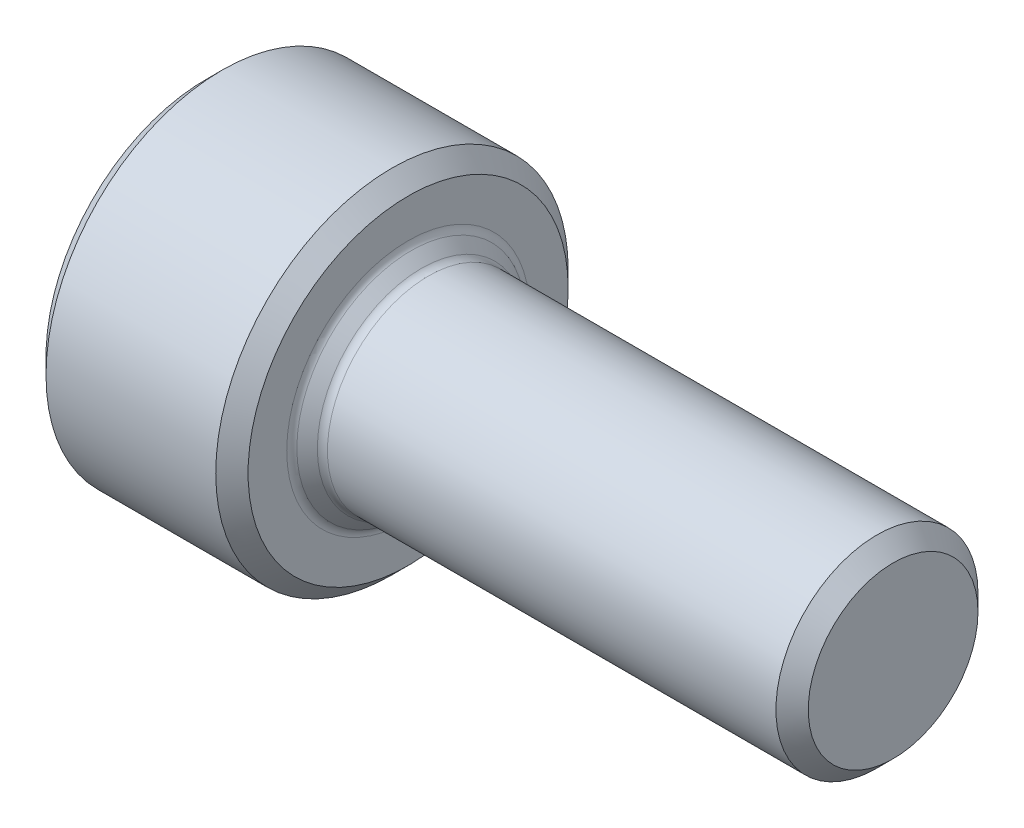
SolidWorks part; units mm, degrees
ref_plane "前基準面" through (0, 0, 0) normal (0, 0, 1) x (1, 0, 0)
ref_plane "上基準面" through (0, 0, 0) normal (0, 1, 0) x (1, 0, 0)
ref_plane "右基準面" through (0, 0, 0) normal (1, 0, 0) x (0, 0, -1)
sketch "草圖1" plane through (0, 0, 0) normal (1, 0, 0) x (0, 0, -1)
  circle A0 centre (0, 0) radius 4.36
  dimension "dk" = 8.72
extrude "伸長1" add sketch "草圖1" against normal blind 5
hole_wizard "Ø1.5 (1.5) 直徑孔1" positions "3D草圖1" profile "草圖2" hole size "Ø1.5" standard "ISO"
sketch3d "3D草圖1"
  circle A0 centre (-5, 0, 0) radius 4.36 construction
  point P0 (-5, 0, 0)
  point P5 (-0.64, 0, 0)
sketch "草圖2" plane through (-5, 0, 0) normal (0, 1, 0) x (0, 0, 1)
  line L0 (0, 0) -> (0, 3.6547)
  line L1 (0, 3.6547) -> (2, 2.5)
  line L2 (2, 2.5) -> (2, 0)
  line L5 (2, 0) -> (0, 0)
  line L10 (0, 3.6547) -> (-2, 2.5) construction
  line L11 (0, -6.35) -> (0, 107.95) construction
  dimension "s" = 4
  dimension "t" = 2.5
  dimension "導頭角度" = 120
sketch "草圖3" plane through (-5, 0, 0) normal (-1, 0, 0) x (0, 0, 1)
  line L1 (2.29, 0) -> (1.145, 1.9832)
  line L2 (1.145, 1.9832) -> (-1.145, 1.9832)
  line L3 (-1.145, 1.9832) -> (-2.29, 0)
  line L4 (-2.29, 0) -> (-1.145, -1.9832)
  line L5 (-1.145, -1.9832) -> (1.145, -1.9832)
  line L6 (1.145, -1.9832) -> (2.29, 0)
  circle A0 centre (0, 0) radius 2.29 construction
  dimension "e" = 4.58
extrude "除料-伸長1" cut sketch "草圖3" against normal blind 2.5
sketch "草圖4" plane through (0, 0, 0) normal (1, 0, 0) x (0, 0, -1)
  circle A0 centre (0, 0) radius 2.5
  dimension "ds" = 5
extrude "伸長2" add sketch "草圖4" along normal blind 12
cosmetic thread "裝飾螺紋線1" parameters "b"=12, "ds-p"=4.2
chamfer "導角1" distance 0.4 angle 45 4 edges at (-5, 0, -4.36) (0, 0, -4.36) (12, 0, -2.5) (0, 0, -2.5)
fillet "圓角1" radius 0.25 2 edges at (0.4, 0, -2.5) (0, 0, -2.9)
